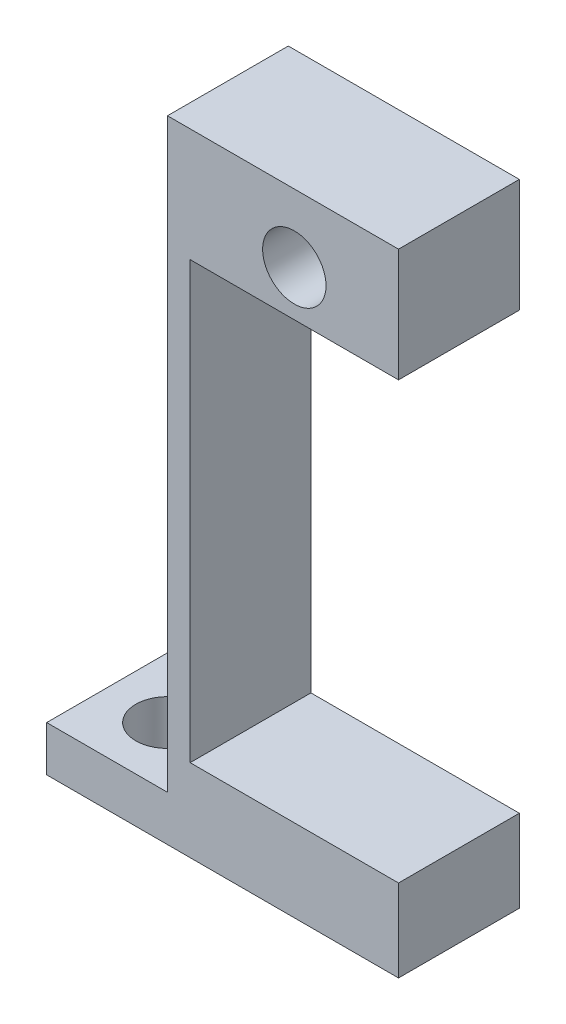
SolidWorks part; units mm, degrees
ref_plane "Front Plane" through (0, 0, 0) normal (0, 0, 1) x (1, 0, 0)
ref_plane "Top Plane" through (0, 0, 0) normal (0, 1, 0) x (1, 0, 0)
ref_plane "Right Plane" through (0, 0, 0) normal (1, 0, 0) x (0, 0, -1)
sketch "Sketch1" plane through (0, 0, 0) normal (0, 1, 0) x (1, 0, 0)
  line L1 (0, 0) -> (-8, 0)
  line L2 (0, 0) -> (0, -8)
  line L3 (0, -8) -> (-8, -8)
  line L4 (-8, 0) -> (-8, -8)
  circle A0 centre (-4, -4) radius 2.1
  dimension "D3" = 4.2
  dimension "D4" = 4
  dimension "D5" = 4
  dimension "D1" = 8
  dimension "D2" = 8
extrude "Boss-Extrude6" add sketch "Sketch1" along normal blind 1.5
sketch "Sketch6" plane through (0, 0, 0) normal (1, 0, 0) x (0, 0, -1)
  line L1 (-8, 0) -> (0, 0)
  line L2 (-8, 0) -> (-8, -1.5)
  line L3 (-8, -1.5) -> (0, -1.5)
  line L4 (0, 0) -> (0, -1.5)
  dimension "D1" = 1.5
extrude "Boss-Extrude7" add sketch "Sketch6" along normal blind 15.3 separate body
sketch "Sketch10" plane through (0, 0, 0) normal (0, -1, 0) x (1, 0, 0)
  line L1 (-8, 8) -> (0, 8)
  line L2 (-8, 8) -> (-8, 0)
  line L3 (-8, 0) -> (0, 0)
  line L4 (0, 8) -> (0, 0)
  circle A0 centre (-4, 4) radius 2.1
  dimension "D1" = 4.2
extrude "Boss-Extrude8" add sketch "Sketch10" along normal blind 1.5
sketch "Sketch11" plane through (0, 0, 0) normal (0, 1, 0) x (1, 0, 0)
  line L0 (15.3, 0) -> (0, 0) construction
  line L1 (0, -8) -> (1.5, -8)
  line L2 (0, -8) -> (0, 0)
  line L3 (0, 0) -> (1.5, 0)
  line L4 (1.5, -8) -> (1.5, 0)
  dimension "D1" = 1.5
extrude "Boss-Extrude9" add sketch "Sketch11" along normal blind 40.3
sketch "Sketch12" plane through (1.5, 0, 0) normal (1, 0, 0) x (0, 0, -1)
  line L0 (0, 40.3) -> (0, 0) construction
  line L1 (-8, 40.3) -> (0, 40.3)
  line L2 (-8, 40.3) -> (-8, 32.8)
  line L3 (-8, 32.8) -> (0, 32.8)
  line L4 (0, 40.3) -> (0, 32.8)
  dimension "D1" = 7.5
extrude "Boss-Extrude10" add sketch "Sketch12" along normal blind 13.8
sketch "Sketch14" plane through (0, 0, 8) normal (0, 0, 1) x (1, 0, 0)
  line L0 (15.3, 32.8) -> (1.5, 32.8) construction
  line L1 (15.3, 40.3) -> (15.3, 32.8) construction
  circle A0 centre (8.4, 35.8) radius 2.1
  dimension "D2" = 6.9
  dimension "D3" = 4.2
  dimension "D1" = 3
extrude "Cut-Extrude1" cut sketch "Sketch14" against normal blind 13.8
sketch "Sketch15" plane through (0, 0, 0) normal (0, 1, 0) x (1, 0, 0)
  line L1 (1.5, 0) -> (15.3, 0)
  line L2 (1.5, 0) -> (1.5, -8)
  line L3 (1.5, -8) -> (15.3, -8)
  line L4 (15.3, 0) -> (15.3, -8)
extrude "Boss-Extrude11" add sketch "Sketch15" along normal blind 3.95
